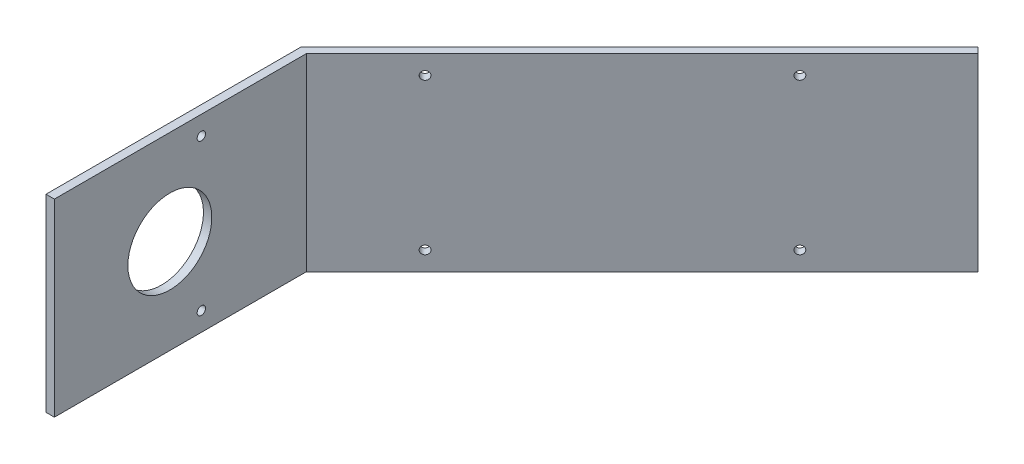
SolidWorks part; units mm, degrees
ref_plane "前视基准面" through (0, 0, 0) normal (0, 0, 1) x (1, 0, 0)
ref_plane "上视基准面" through (0, 0, 0) normal (0, 1, 0) x (1, 0, 0)
ref_plane "右视基准面" through (0, 0, 0) normal (1, 0, 0) x (0, 0, -1)
sketch "草图1" plane through (0, 0, 0) normal (0, 1, 0) x (1, 0, 0)
  line L0 (0, 0) -> (0, 120)
  line L1 (0, 120) -> (160, 280)
  line L2 (-4, 0) -> (-4, 121.6569)
  line L3 (-4, 121.6569) -> (157.1716, 282.8284)
  line L4 (0, 0) -> (-4, 0)
  line L5 (160, 280) -> (157.1716, 282.8284)
  dimension "D1" = 135
  dimension "D2" = 280
  dimension "D3" = 160
  dimension "D4" = 4
extrude "凸台-拉伸1" add sketch "草图1" along normal mid plane 90
sketch "草图3" plane through (-4, 0, 0) normal (-1, 0, 0) x (0, 0, 1)
  line L0 (0, 45) -> (0, -45) construction
  line L2 (-121.6569, -45) -> (0, -45) construction
  circle A0 centre (-70, -36) radius 2
  dimension "D1" = 4
  dimension "D2" = 70
  dimension "D3" = 9
extrude "切除-拉伸2" cut sketch "草图3" against normal blind 90
sketch "草图4" plane through (-60, 0, -60) normal (0.7071, 0, 0.7071) x (0.7071, 0, -0.7071)
  line L0 (84.8528, -45) -> (311.127, -45) construction
  line L3 (84.8528, 45) -> (84.8528, -45) construction
  line L4 (311.127, 45) -> (311.127, -45) construction
  circle A0 centre (124.8528, -36) radius 2
  circle A1 centre (251.127, -36) radius 2
  dimension "D1" = 4
  dimension "D2" = 4
  dimension "D3" = 9
  dimension "D4" = 40
  dimension "D5" = 60
extrude "切除-拉伸3" cut sketch "草图4" against normal blind 90
mirror "镜向1" about plane through (0, 0, 0) normal (0, 1, 0) of "切除-拉伸2", "切除-拉伸3"
sketch "草图5" plane through (-4, 0, 0) normal (-1, 0, 0) x (0, 0, 1)
  circle A0 centre (-55, 0) radius 20
  dimension "D1" = 40
  dimension "D2" = 55
extrude "切除-拉伸4" cut sketch "草图5" against normal blind 90
